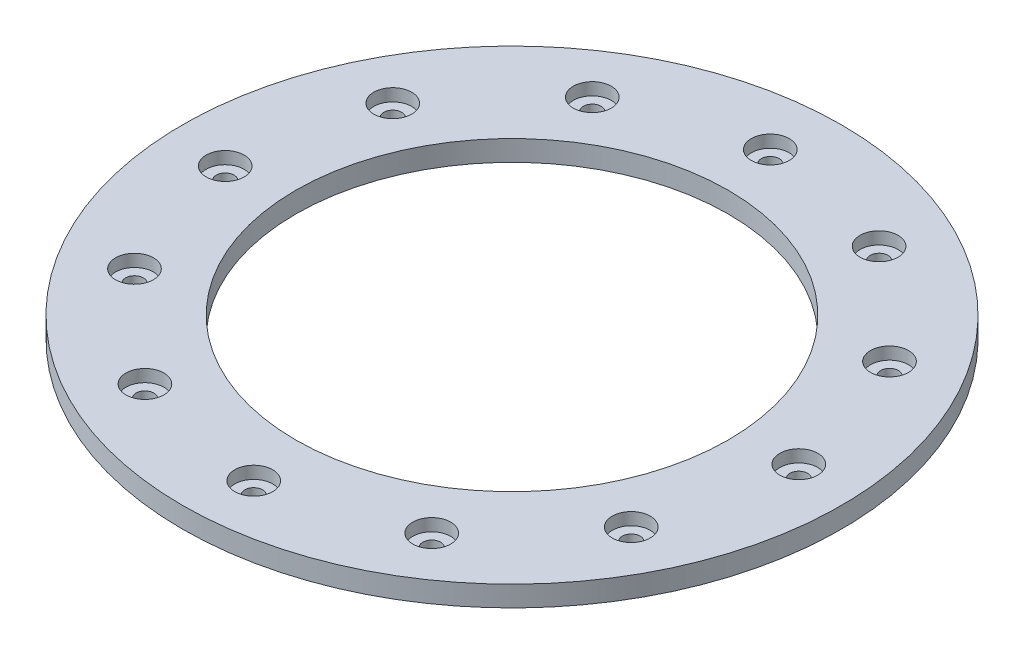
SolidWorks part; units mm, degrees
material "1023 Carbon Steel Sheet (SS)"
ref_plane "Front Plane" through (0, 0, 0) normal (0, 0, 1) x (1, 0, 0)
ref_plane "Top Plane" through (0, 0, 0) normal (0, 1, 0) x (1, 0, 0)
ref_plane "Right Plane" through (0, 0, 0) normal (1, 0, 0) x (0, 0, -1)
sketch "Sketch1" plane through (0, 0, 0) normal (0, 1, 0) x (1, 0, 0)
  line L0 (-90.5237, 46.1304) -> (-59.4062, 30.2731) construction
  line L1 (0, 0) -> (0, 97.5433) construction
  circle A0 centre (0, 0) radius 101.6
  circle A1 centre (0, 0) radius 66.675
  circle A3 centre (0, 0) radius 84.1375 construction
  circle A4 centre (-74.965, 38.2017) radius 0.254
  point P7 (-74.965, 38.2017)
extrude "Boss-Extrude1" add sketch "Sketch1" along normal blind 6.35
hole_wizard "CBORE for M5 Hex Head Machine Screw1" positions "Sketch6" profile "Sketch7" counterbore size "M5" standard "ANSI Metric" end condition through all
sketch "Sketch6" plane through (0, 6.35, 0) normal (0, 1, 0) x (1, 0, 0)
  point P0 (-74.965, 38.2017)
sketch "Sketch7" plane through (-74.965, 6.35, -38.2017) normal (1, 0, 0) x (0, 0, 1)
  line L0 (0, 0) -> (0, 6.35)
  line L1 (0, 6.35) -> (2.75, 6.35)
  line L3 (2.75, 6.35) -> (2.75, 3.8)
  line L4 (2.75, 3.8) -> (5.855, 3.8)
  line L5 (5.855, 3.8) -> (5.855, 0)
  line L7 (5.855, 0) -> (0, 0)
  line L11 (0, -6.35) -> (0, 107.95) construction
  dimension "Thru Hole Dia." = 5.5
  dimension "Thru Hole Depth" = 6.35
  dimension "C'Bore Dia." = 11.71
  dimension "C'Bore Depth" = 3.8
pattern_circular "CirPattern1" count 12 over 360 about axis through (0, 0, 0) along (0, 1, 0) of "CBORE for M5 Hex Head Machine Screw1"
